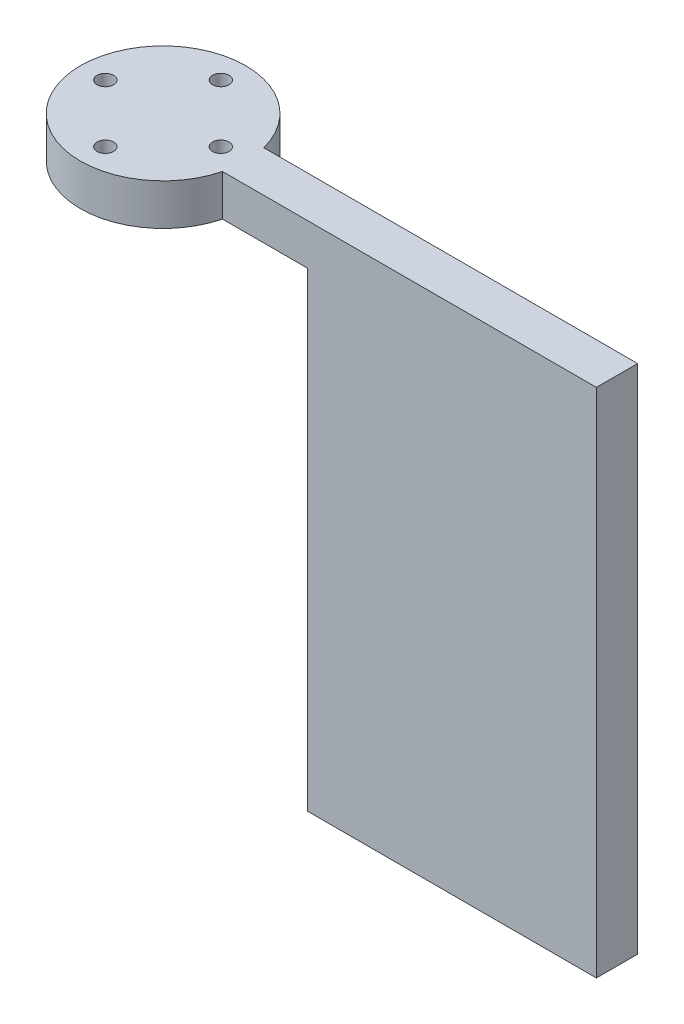
SolidWorks part; units mm, degrees
ref_plane "Front Plane" through (0, 0, 0) normal (0, 0, 1) x (1, 0, 0)
ref_plane "Top Plane" through (0, 0, 0) normal (0, 1, 0) x (1, 0, 0)
ref_plane "Right Plane" through (0, 0, 0) normal (1, 0, 0) x (0, 0, -1)
sketch "Sketch1" plane through (0, 0, 0) normal (0, 0, 1) x (1, 0, 0)
  line L1 (0, 0) -> (35, 0)
  line L2 (0, 0) -> (0, 62)
  line L3 (0, 62) -> (35, 62)
  line L4 (35, 0) -> (35, 62)
  line L5 (0, 62) -> (-10, 62)
  line L6 (0, 62) -> (0, 57)
  line L7 (0, 57) -> (-10, 57)
  line L8 (-10, 62) -> (-10, 57)
  dimension "D1" = 35
  dimension "D2" = 62
  dimension "D3" = 10
  dimension "D4" = 5
extrude "Boss-Extrude1" add sketch "Sketch1" along normal mid plane 5 contours L1 L4 L3 L2 | L5 L8 L7 L2
sketch "Sketch2" plane through (0, 62, 0) normal (0, 1, 0) x (1, 0, 0)
  line L0 (-10, -2.5) -> (-10, 2.5) construction
  line L1 (-10, 2.5) -> (-20.3169, 2.5)
  line L2 (-10, 2.5) -> (-10, 0)
  line L3 (-10, 2.5) -> (35, 2.5) construction
  circle A0 centre (-20.02, 0) radius 10.02
  circle A1 centre (-20.02, 0) radius 7 construction
  circle A2 centre (-20.02, 7) radius 1
  circle A3 centre (-27.02, 0) radius 1
  circle A4 centre (-20.02, -7) radius 1
  circle A5 centre (-13.02, 0) radius 1
  line M3 (-10, 2.5) -> (-10, -2.5)
  dimension "D1" = 20.04
  dimension "D2" = 14
  dimension "D3" = 2
extrude "Boss-Extrude2" add sketch "Sketch2" against normal blind 5 separate body contours A0 A5 A4 A3 A2 | A0 L1 M3
sketch "Sketch3" plane through (0, 62, 0) normal (0, 1, 0) x (1, 0, 0)
  line L0 (-10, 0) -> (-10, -2.5)
  line L1 (-10, -2.5) -> (-10.3169, -2.5)
  arc A0 (-10.3169, 2.5) -> (-10, 0) centre (-20.02, 0) ccw construction
  arc A1 (-10.3169, -2.5) -> (-10, 0) centre (-20.02, 0) ccw
extrude "Boss-Extrude3" add sketch "Sketch3" against normal blind 5
